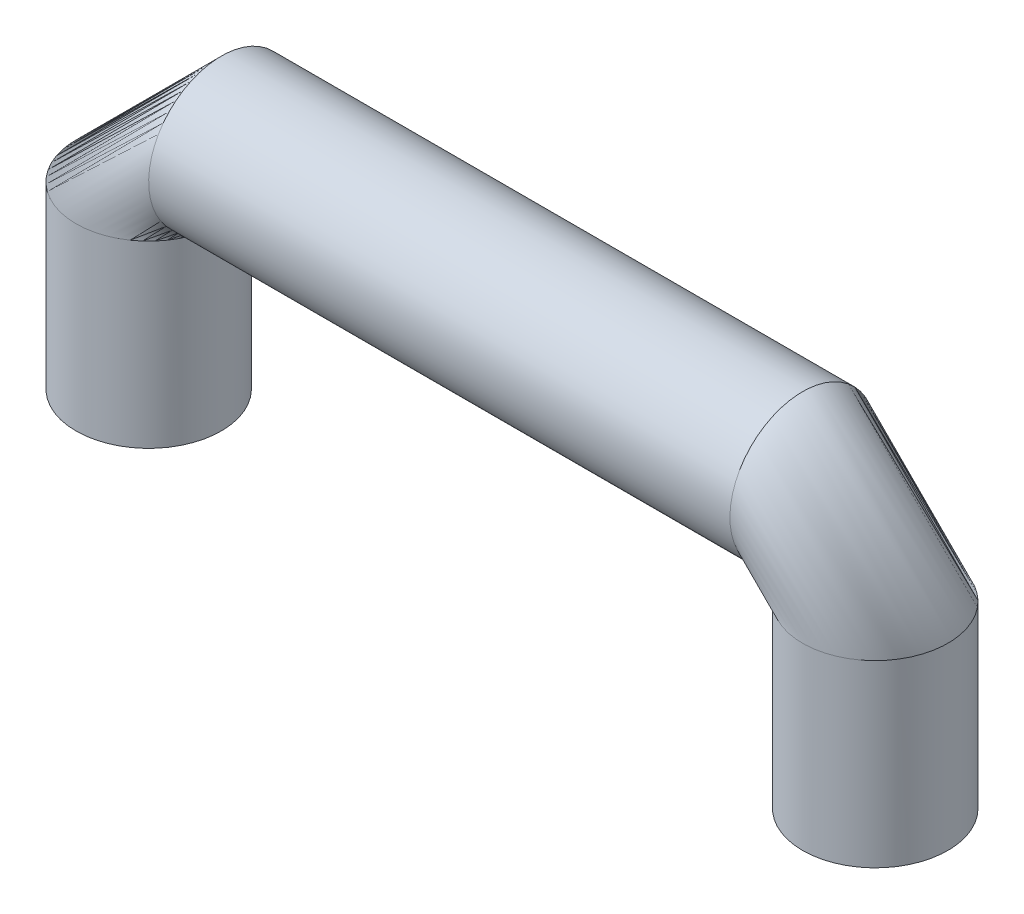
SolidWorks part; units mm, degrees
material "Cast Carbon Steel"
ref_plane "Front Plane" through (0, 0, 0) normal (0, 0, 1) x (1, 0, 0)
ref_plane "Top Plane" through (0, 0, 0) normal (0, 1, 0) x (1, 0, 0)
ref_plane "Right Plane" through (0, 0, 0) normal (1, 0, 0) x (0, 0, -1)
sketch "Sketch1" plane through (0, 0, 0) normal (0, 0, 1) x (1, 0, 0)
  line L0 (0, 0) -> (0, 62.738)
  line L1 (25.4, 88.138) -> (228.6, 88.138)
  line L2 (254, 62.738) -> (254, 0)
  arc A0 (0, 62.738) -> (25.4, 88.138) centre (25.4, 62.738) cw
  arc A1 (228.6, 88.138) -> (254, 62.738) centre (228.6, 62.738) cw
  dimension "D2" = 25.4
  dimension "D1" = 62.738
  dimension "D3" = 254
sweep "Sweep5" add path "Sketch1" circular profile diameter 50.8 parameters "D3"=50.8
